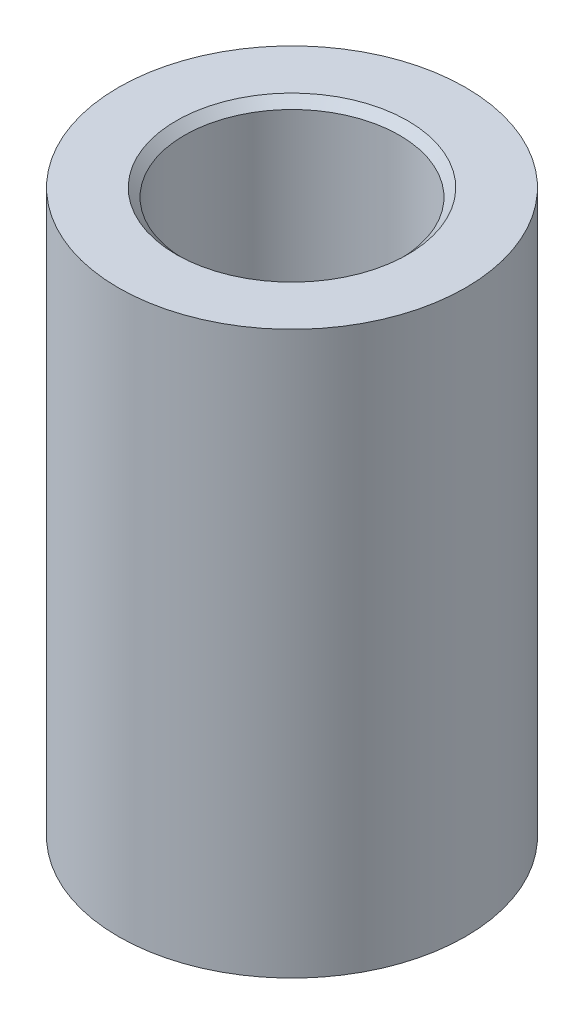
SolidWorks part; units mm, degrees
ref_plane "Front Plane" through (0, 0, 0) normal (0, 0, 1) x (1, 0, 0)
ref_plane "Top Plane" through (0, 0, 0) normal (0, 1, 0) x (1, 0, 0)
ref_plane "Right Plane" through (0, 0, 0) normal (1, 0, 0) x (0, 0, -1)
sketch "Sketch1" plane through (0, 0, 0) normal (0, 1, 0) x (1, 0, 0)
  circle A0 centre (0, 0) radius 5.1625
  circle A1 centre (0, 0) radius 8.3375
  dimension "D1" = 3.175
extrude "Boss-Extrude1" add sketch "Sketch1" along normal blind 26.9875
chamfer "Chamfer1" distance 0.4 angle 45 2 edges at (0, 0, 5.1625) (0, 26.9875, 5.1625)
